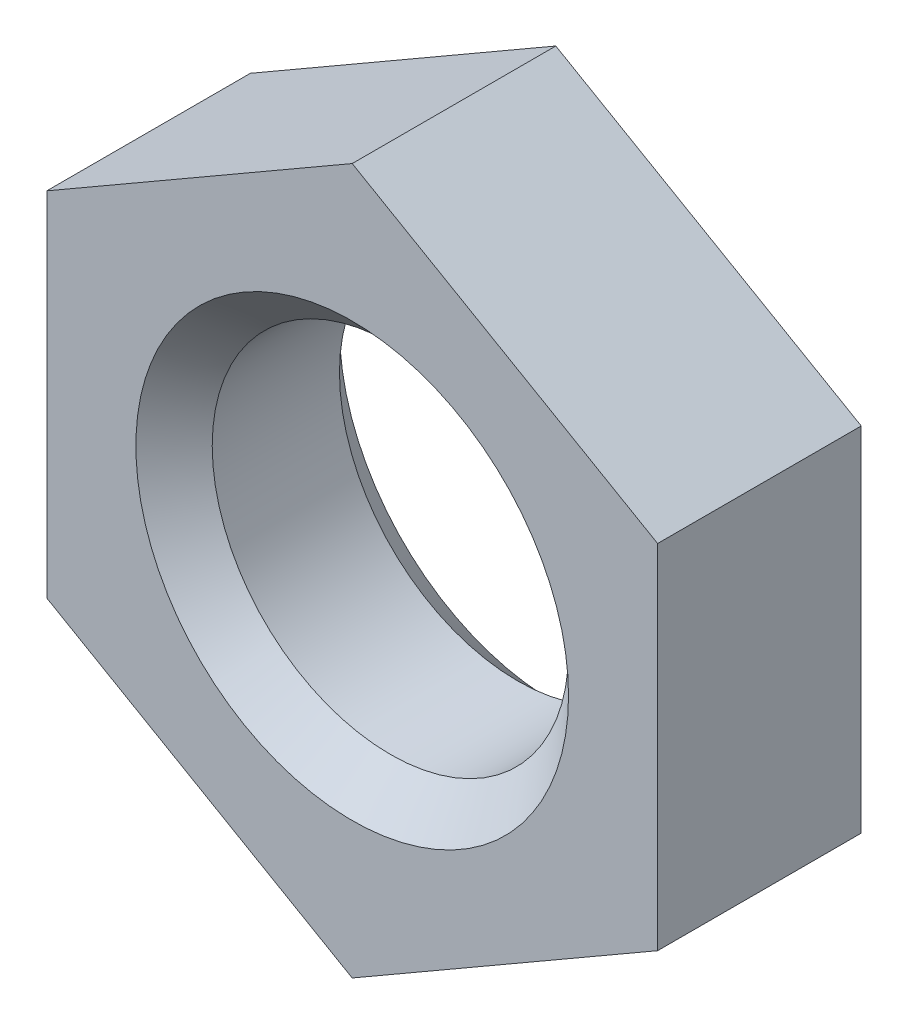
SolidWorks part; units mm, degrees
ref_plane "Спереди" through (0, 0, 0) normal (0, 0, 1) x (1, 0, 0)
ref_plane "Сверху" through (0, 0, 0) normal (0, 1, 0) x (1, 0, 0)
ref_plane "Справа" through (0, 0, 0) normal (1, 0, 0) x (0, 0, -1)
sketch "Эскиз1" plane through (0, 0, 0) normal (0, 0, 1) x (1, 0, 0)
  line L0 (0, 0) -> (0, 50000) construction
  line L1 (0, 13.8564) -> (-12, 6.9282)
  line L2 (-12, 6.9282) -> (-12, -6.9282)
  line L3 (-12, -6.9282) -> (0, -13.8564)
  line L4 (0, -13.8564) -> (12, -6.9282)
  line L5 (12, -6.9282) -> (12, 6.9282)
  line L6 (12, 6.9282) -> (0, 13.8564)
  line L7 (0, 0) -> (-50000, 0) construction
  circle A0 centre (0, 0) radius 12 construction
  dimension "D1" = 24
extrude "Бобышка-Вытянуть1" add sketch "Эскиз1" along normal blind 8
sketch "Эскиз4" plane through (0, 0, 0) normal (0, 0, -1) x (-1, 0, 0)
  point P0 (0, 0)
hole_wizard "Отверстие обработанное метчиком M161" positions "Эскиз4" profile "Эскиз3" tap size "M16" standard "ISO" end condition up to next
sketch "Эскиз3" plane through (0, 0, 0) normal (1, 0, 0) x (0, 1, 0)
  line L0 (0, 0) -> (0, 8)
  line L1 (0, 8) -> (7, 8)
  line L2 (7, 8) -> (7, 0)
  line L5 (7, 0) -> (0, 0)
  line L11 (0, -6.35) -> (0, 107.95) construction
  dimension "Диаметр проходного сверла" = 14
  dimension "Глубина проходного сверла" = 8
cosmetic thread "Отверстие резьбы1" parameters "D2"=16
chamfer "Фаска1" distance 1.5 angle 45 2 edges at (7, 0, 8) (-7, 0, 0)
